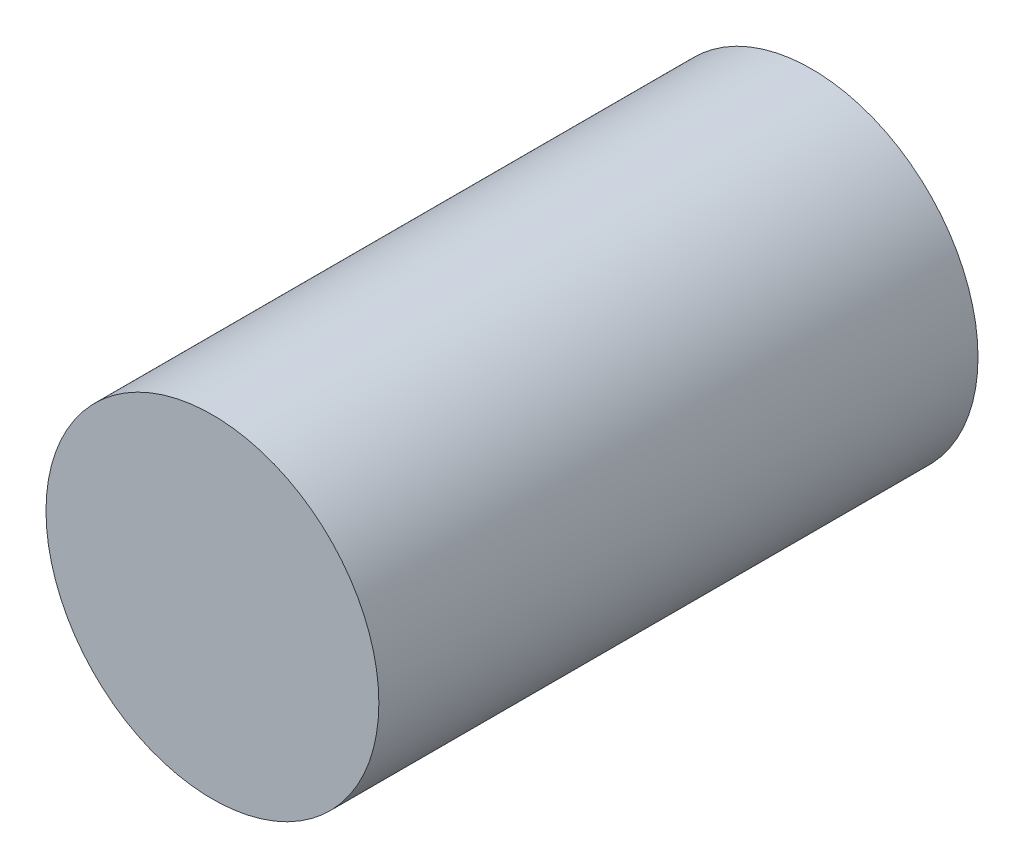
SolidWorks part; units mm, degrees
ref_plane "Front Plane" through (0, 0, 0) normal (0, 0, 1) x (1, 0, 0)
ref_plane "Top Plane" through (0, 0, 0) normal (0, 1, 0) x (1, 0, 0)
ref_plane "Right Plane" through (0, 0, 0) normal (1, 0, 0) x (0, 0, -1)
sketch "草圖1" plane through (0, 0, 0) normal (0, 0, 1) x (1, 0, 0)
  circle A0 centre (0, 0) radius 5
extrude "填料-伸長1" add sketch "草圖1" along normal blind 18
